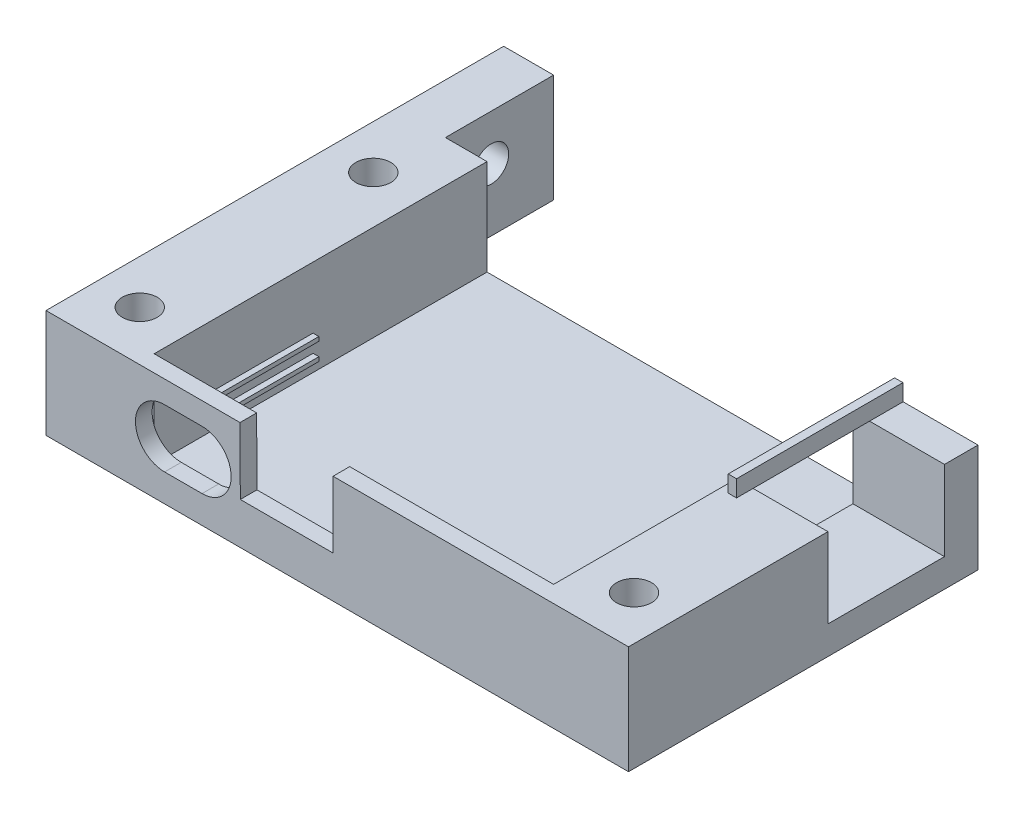
SolidWorks part; units mm, degrees
ref_plane "前视基准面" through (0, 0, 0) normal (0, 0, 1) x (1, 0, 0)
ref_plane "上视基准面" through (0, 0, 0) normal (0, 1, 0) x (1, 0, 0)
ref_plane "右视基准面" through (0, 0, 0) normal (1, 0, 0) x (0, 0, -1)
other "Configuration Table"
sketch "草图1" plane through (0, 0, 0) normal (0, 1, 0) x (1, 0, 0)
  line L1 (-30.5608, 21.4548) -> (17.4392, 21.4548)
  line L2 (-30.5608, 21.4548) -> (-30.5608, -18.5452)
  line L3 (-30.5608, -18.5452) -> (17.4392, -18.5452)
  line L4 (17.4392, 21.4548) -> (17.4392, -18.5452)
  line L5 (-30.5608, 21.4548) -> (-41.5608, 21.4548)
  line L6 (-30.5608, 21.4548) -> (-30.5608, -18.5452)
  line L7 (-30.5608, -18.5452) -> (-41.5608, -18.5452)
  line L8 (-41.5608, 21.4548) -> (-41.5608, -18.5452)
  line L9 (17.4392, 21.4548) -> (28.4392, 21.4548)
  line L10 (17.4392, 21.4548) -> (17.4392, -18.5452)
  line L11 (17.4392, -18.5452) -> (28.4392, -18.5452)
  line L12 (28.4392, 21.4548) -> (28.4392, -18.5452)
  line L13 (-41.5608, -18.5452) -> (28.4392, -18.5452)
  line L14 (-41.5608, -18.5452) -> (-41.5608, -20.5452)
  line L15 (-41.5608, -20.5452) -> (28.4392, -20.5452)
  line L16 (28.4392, -18.5452) -> (28.4392, -20.5452)
  dimension "D1" = 40
  dimension "D2" = 48
  dimension "D3" = 11
  dimension "D4" = 2
extrude "凸台-拉伸1" add sketch "草图1" along normal blind 13 contours L6 L5 L8 L7 | L14 L13 L16 L15 | L10 L9 L12 L11
sketch "草图2" plane through (-30.5608, 0, 0) normal (1, 0, 0) x (0, 0, -1)
  line L0 (-18.5452, 13) -> (-18.5452, 0) construction
  line L1 (-18.5452, 1.5) -> (21.4548, 1.5)
  line L2 (-18.5452, 1.5) -> (-18.5452, 0)
  line L3 (-18.5452, 0) -> (21.4548, 0)
  line L4 (21.4548, 1.5) -> (21.4548, 0)
  dimension "D1" = 1.5
extrude "凸台-拉伸2" add sketch "草图2" along normal blind 48
sketch "草图3" plane through (-30.5608, 0, 0) normal (1, 0, 0) x (0, 0, -1)
  line L0 (21.4548, 1.5) -> (-18.5452, 1.5) construction
  line L1 (-11.4534, 5.6) -> (0.5466, 5.6)
  line L2 (-11.4534, 5.6) -> (-11.4534, 5.1)
  line L3 (-11.4534, 5.1) -> (0.5466, 5.1)
  line L4 (0.5466, 5.6) -> (0.5466, 5.1)
  line L5 (-11.4534, 3.5) -> (0.5466, 3.5)
  line L6 (-11.4534, 3.5) -> (-11.4534, 3)
  line L7 (-11.4534, 3) -> (0.5466, 3)
  line L8 (0.5466, 3.5) -> (0.5466, 3)
  point P10 (0.5466, 5.35)
  dimension "D1" = 0.5
  dimension "D3" = 1.6
  dimension "D4" = 12
  dimension "D5" = 1.5
extrude "凸台-拉伸3" add sketch "草图3" along normal blind 0.7
sketch "草图4" plane through (17.4392, 0, 0) normal (-1, 0, 0) x (0, 0, 1)
  line L0 (18.5452, 13) -> (18.5452, 1.5) construction
  line L1 (-1.4548, 2.9049) -> (18.5452, 2.9049)
  line L2 (-1.4548, 2.9049) -> (-1.4548, 3.4)
  line L3 (-1.4548, 3.4) -> (18.5452, 3.4)
  line L4 (18.5452, 2.9049) -> (18.5452, 3.4)
  line L6 (-1.4548, 5.4951) -> (18.5452, 5.4951)
  line L7 (-1.4548, 5.4951) -> (-1.4548, 5)
  line L8 (-1.4548, 5) -> (18.5452, 5)
  line L9 (18.5452, 5.4951) -> (18.5452, 5)
  line L11 (-21.4548, 1.5) -> (18.5452, 1.5) construction
  dimension "D1" = 20
  dimension "D2" = 0.4951
  dimension "D3" = 1.6
  dimension "D4" = 1.9
extrude "凸台-拉伸4" add sketch "草图4" along normal blind 0.7
sketch "草图5" plane through (0, 0, 0) normal (0, -1, 0) x (-1, 0, 0)
  line L0 (-28.4392, 21.4548) -> (-28.4392, -20.5452) construction
  line L7 (-23.1392, 8.5243) -> (-18.8392, 11.0069)
  line L8 (-18.8392, 11.0069) -> (-18.8392, 15.9722)
  line L9 (-18.8392, 15.9722) -> (-23.1392, 18.4548)
  line L10 (-23.1392, 18.4548) -> (-27.4392, 15.9722)
  line L11 (-27.4392, 15.9722) -> (-27.4392, 11.0069)
  line L12 (-27.4392, 11.0069) -> (-23.1392, 8.5243)
  line L13 (36.2608, 8.5243) -> (40.5608, 11.0069)
  line L14 (40.5608, 11.0069) -> (40.5608, 15.9722)
  line L15 (40.5608, 15.9722) -> (36.2608, 18.4548)
  line L16 (36.2608, 18.4548) -> (31.9608, 15.9722)
  line L17 (31.9608, 15.9722) -> (31.9608, 11.0069)
  line L18 (31.9608, 11.0069) -> (36.2608, 8.5243)
  line L19 (36.2608, -19.5452) -> (40.5608, -17.0626)
  line L20 (40.5608, -17.0626) -> (40.5608, -12.0974)
  line L21 (40.5608, -12.0974) -> (36.2608, -9.6148)
  line L22 (36.2608, -9.6148) -> (31.9608, -12.0974)
  line L23 (31.9608, -12.0974) -> (31.9608, -17.0626)
  line L24 (31.9608, -17.0626) -> (36.2608, -19.5452)
  line L25 (-23.1392, -19.5452) -> (-18.8392, -17.0626)
  line L26 (-18.8392, -17.0626) -> (-18.8392, -12.0974)
  line L27 (-18.8392, -12.0974) -> (-23.1392, -9.6148)
  line L28 (-23.1392, -9.6148) -> (-27.4392, -12.0974)
  line L29 (-27.4392, -12.0974) -> (-27.4392, -17.0626)
  line L30 (-27.4392, -17.0626) -> (-23.1392, -19.5452)
  line L31 (41.5608, 21.4548) -> (41.5608, -20.5452) construction
  line L33 (-28.4392, 21.4548) -> (41.5608, 21.4548) construction
  line L34 (41.5608, -20.5452) -> (-28.4392, -20.5452) construction
  circle A0 centre (-23.1392, 13.4895) radius 4.3 construction
  circle A1 centre (36.2608, 13.4895) radius 4.3 construction
  circle A2 centre (36.2608, -14.58) radius 4.3 construction
  circle A3 centre (-23.1392, -14.58) radius 4.3 construction
  point P25 (0, 0)
  point P33 (0, 0)
  point P34 (0, 0)
  point P35 (34.447, 14.6816)
  point P36 (0, 0)
  point P37 (0, 0)
  point P38 (0, 0)
  point P39 (0, 0)
  point P40 (0, 0)
  point P41 (0, 0)
  point P42 (0, 0)
  point P43 (0, 0)
  point P44 (0, 0)
  point P45 (0, 0)
  point P46 (0, 0)
  point P47 (0, 0)
  point P48 (0, 0)
  point P49 (0, 0)
  point P50 (0, 0)
  point P51 (-22.3029, -15.2718)
  point P52 (-21.4523, -13.3668)
  dimension "D1" = 8.6
  dimension "D2" = 1
  dimension "D3" = 1
  dimension "D4" = 3
  dimension "D5" = 1
extrude "切除-拉伸1" cut sketch "草图5" against normal blind 6 contours L29 L30 L25 L26 L27 L28 | L23 L24 L19 L20 L21 L22 | L17 L18 L13 L14 L15 L16
sketch "草图10" plane through (0, 6, 0) normal (0, -1, 0) x (1, 0, 0)
  line L12 (27.4392, -11.0069) -> (23.1392, -8.5243)
  line L13 (23.1392, -8.5243) -> (18.8392, -11.0069)
  line L14 (18.8392, -11.0069) -> (18.8392, -15.9722)
  line L15 (18.8392, -15.9722) -> (23.1392, -18.4548)
  line L16 (23.1392, -18.4548) -> (27.4392, -15.9722)
  line L17 (27.4392, -15.9722) -> (27.4392, -11.0069)
  line L18 (27.4392, -11.0069) -> (23.1392, -8.5243)
  line L19 (23.1392, -8.5243) -> (18.8392, -11.0069)
  line L20 (18.8392, -11.0069) -> (18.8392, -15.9722)
  line L21 (18.8392, -15.9722) -> (23.1392, -18.4548)
  line L22 (23.1392, -18.4548) -> (27.4392, -15.9722)
  line L23 (27.4392, -15.9722) -> (27.4392, -11.0069)
  line L30 (-31.9608, 17.0626) -> (-36.2608, 19.5452)
  line L31 (-36.2608, 19.5452) -> (-40.5608, 17.0626)
  line L32 (-40.5608, 17.0626) -> (-40.5608, 12.0974)
  line L33 (-40.5608, 12.0974) -> (-36.2608, 9.6148)
  line L34 (-36.2608, 9.6148) -> (-31.9608, 12.0974)
  line L35 (-31.9608, 12.0974) -> (-31.9608, 17.0626)
  line L36 (-31.9608, 17.0626) -> (-36.2608, 19.5452)
  line L37 (-36.2608, 19.5452) -> (-40.5608, 17.0626)
  line L38 (-40.5608, 17.0626) -> (-40.5608, 12.0974)
  line L39 (-40.5608, 12.0974) -> (-36.2608, 9.6148)
  line L40 (-36.2608, 9.6148) -> (-31.9608, 12.0974)
  line L41 (-31.9608, 12.0974) -> (-31.9608, 17.0626)
  line L48 (27.4392, 17.0626) -> (23.1392, 19.5452)
  line L49 (23.1392, 19.5452) -> (18.8392, 17.0626)
  line L50 (18.8392, 17.0626) -> (18.8392, 12.0974)
  line L51 (18.8392, 12.0974) -> (23.1392, 9.6148)
  line L52 (23.1392, 9.6148) -> (27.4392, 12.0974)
  line L53 (27.4392, 12.0974) -> (27.4392, 17.0626)
  line L54 (27.4392, 17.0626) -> (23.1392, 19.5452)
  line L55 (23.1392, 19.5452) -> (18.8392, 17.0626)
  line L56 (18.8392, 17.0626) -> (18.8392, 12.0974)
  line L57 (18.8392, 12.0974) -> (23.1392, 9.6148)
  line L58 (23.1392, 9.6148) -> (27.4392, 12.0974)
  line L59 (27.4392, 12.0974) -> (27.4392, 17.0626)
  line L64 (-36.2608, 19.5452) -> (-36.2608, 9.6148)
  line L65 (23.1392, 19.5452) -> (23.1392, 9.6148)
  line L66 (-31.9608, -11.0069) -> (-36.2608, -8.5243)
  line L67 (-36.2608, -8.5243) -> (-40.5608, -11.0069)
  line L68 (-40.5608, -11.0069) -> (-40.5608, -15.9722)
  line L69 (-40.5608, -15.9722) -> (-36.2608, -18.4548)
  line L70 (-36.2608, -18.4548) -> (-31.9608, -15.9722)
  line L71 (-31.9608, -15.9722) -> (-31.9608, -11.0069)
  line L72 (-31.9608, -11.0069) -> (-36.2608, -8.5243)
  line L73 (-36.2608, -8.5243) -> (-40.5608, -11.0069)
  line L74 (-40.5608, -11.0069) -> (-40.5608, -15.9722)
  line L75 (-40.5608, -15.9722) -> (-36.2608, -18.4548)
  line L76 (-36.2608, -18.4548) -> (-31.9608, -15.9722)
  line L77 (-31.9608, -15.9722) -> (-31.9608, -11.0069)
  line L78 (23.1392, -8.5243) -> (23.1392, -18.4548)
  line L80 (-36.2608, -18.4548) -> (-36.2608, -8.5243)
  circle A0 centre (-36.2608, 14.58) radius 2.1
  circle A1 centre (-36.2608, -13.4895) radius 2.1
  circle A2 centre (23.1392, -13.4895) radius 2.1
  circle A3 centre (23.1392, 14.58) radius 2.1
  dimension "D5" = 4.2
  dimension "D6" = 4.2
  dimension "D1" = 0
  dimension "D2" = 0
  dimension "D3" = 0
  dimension "D4" = 0
extrude "切除-拉伸2" cut sketch "草图10" against normal blind 9 contours L80 A1 | L64 A0 | L64 A0 | L80 A1 | A3
sketch "草图12" plane through (0, 0, 20.5452) normal (0, 0, 1) x (1, 0, 0)
  line L3 (-24.9292, 7.5029) -> (-24.9292, 7.1457)
  line L4 (-27.3108, 3.325) -> (-22.8108, 3.325)
  line L5 (-22.8108, 10.325) -> (-27.3108, 10.325)
  arc A0 (-27.3108, 10.325) -> (-27.3108, 3.325) centre (-27.3108, 6.825) ccw
  arc A1 (-22.8108, 3.325) -> (-22.8108, 10.325) centre (-22.8108, 6.825) ccw
  point P0 (-30.8108, 6.825)
  point P1 (-19.3108, 6.825)
  point P9 (-24.9292, 7.1457)
  point P17 (0, 0)
  dimension "D2" = 11.5
  dimension "D1" = 7
extrude "切除-拉伸3" cut sketch "草图12" against normal blind 2
sketch "草图13" plane through (0, 0, 20.5452) normal (0, 0, 1) x (1, 0, 0)
  line L0 (-41.5608, 13) -> (28.4392, 13) construction
  line L1 (-18.2458, 13) -> (-18.2108, 5.01)
  line L2 (-18.2458, 16.595) -> (-18.2458, 5.095) construction
  line L3 (-18.2108, 5.01) -> (-7.063, 5.01)
  line L4 (16.4392, 5.01) -> (-29.5608, 5.01) construction
  line L5 (-7.063, 5.01) -> (-7.0658, 13)
  line L6 (-7.0658, 16.595) -> (-7.0658, 5.095) construction
  line L7 (-18.2458, 13) -> (-7.0658, 13)
extrude "切除-拉伸4" cut sketch "草图13" against normal blind 2 contours L7 L5 L3 L1
sketch "草图17" plane through (0, 13, 0) normal (0, 1, 0) x (1, 0, 0)
  line L8 (17.4392, 21.4548) -> (17.4392, -18.5452) construction
  line L9 (18.4392, 21.4391) -> (19.4392, 21.4391)
  line L10 (18.4392, 21.4391) -> (18.4392, 1.4391)
  line L11 (18.4392, 1.4391) -> (19.4392, 1.4391)
  line L12 (19.4392, 21.4391) -> (19.4392, 1.4391)
  dimension "D1" = 1
  dimension "D2" = 20
  dimension "D3" = 1
extrude "凸台-拉伸6" add sketch "草图17" along normal blind 2
sketch "草图21" plane through (0, 0, -21.4548) normal (0, 0, -1) x (-1, 0, 0)
  line L0 (30.5608, 13) -> (41.5608, 13) construction
  line L1 (35.5608, 13) -> (41.5608, 13)
  line L2 (35.5608, 13) -> (35.5608, 0)
  line L3 (35.5608, 0) -> (41.5608, 0)
  line L4 (41.5608, 13) -> (41.5608, 0)
  dimension "D1" = 6
extrude "凸台-拉伸8" add sketch "草图21" along normal blind 13
sketch "草图23" plane through (-35.5608, 0, 0) normal (1, 0, 0) x (0, 0, -1)
  circle A0 centre (26.9548, 7.5) radius 2.1
extrude "切除-拉伸7" cut sketch "草图23" against normal blind 6
sketch "草图25" plane through (28.4392, 0, 0) normal (1, 0, 0) x (0, 0, -1)
  line L0 (21.4548, 0) -> (-20.5452, 0) construction
  line L1 (3.4248, 13) -> (17.4248, 13)
  line L2 (3.4248, 13) -> (3.4248, 3.4)
  line L3 (3.4248, 3.4) -> (17.4248, 3.4)
  line L4 (17.4248, 13) -> (17.4248, 3.4)
  line L5 (21.4548, 13) -> (21.4548, 0) construction
  line L6 (21.4548, 13) -> (-20.5452, 13) construction
  dimension "D1" = 3.4
  dimension "D2" = 4.03
  dimension "D3" = 14
extrude "切除-拉伸8" cut sketch "草图25" against normal blind 11
